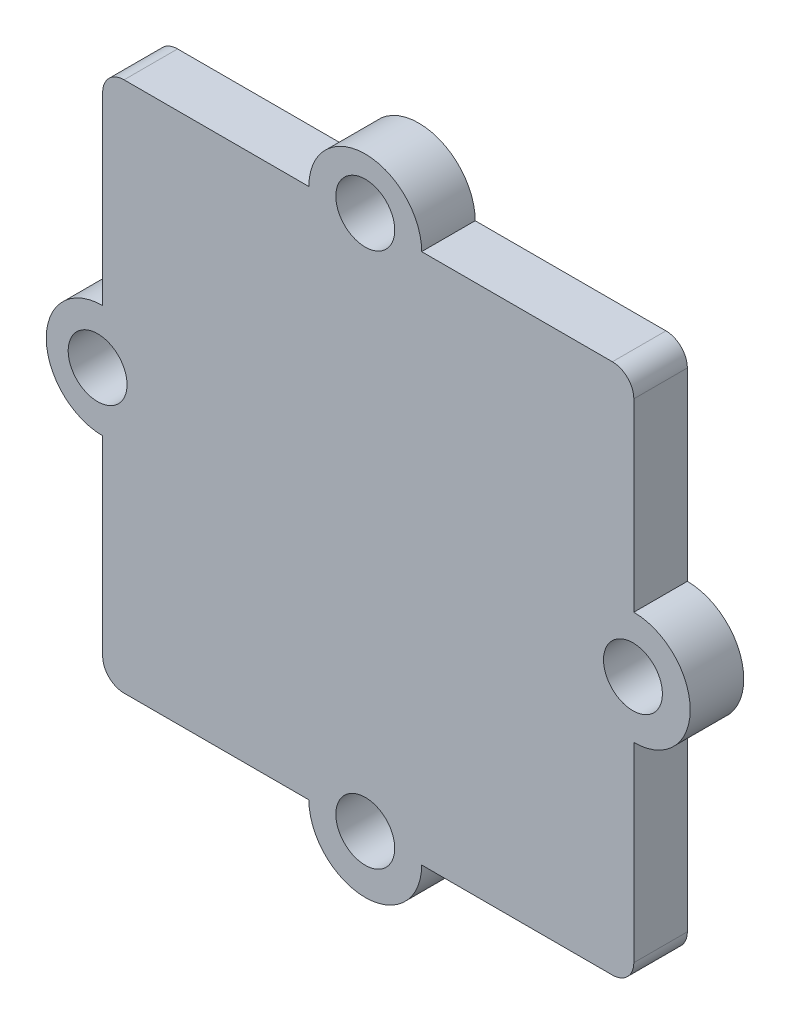
SolidWorks part; units mm, degrees
ref_plane "Front Plane" through (0, 0, 0) normal (0, 0, 1) x (1, 0, 0)
ref_plane "Top Plane" through (0, 0, 0) normal (0, 1, 0) x (1, 0, 0)
ref_plane "Right Plane" through (0, 0, 0) normal (1, 0, 0) x (0, 0, -1)
ref_plane "Plane1" through (0, 0, -2) normal (0, 0, -1) x (-1, 0, 0)
sketch "Sketch1" plane through (0, 0, -2) normal (0, 0, -1) x (-1, 0, 0)
  line L0 (-1.9169, 8.9003) -> (-9.843, 8.9003)
  line L1 (-9.843, 8.9003) -> (-9.843, 1.1965)
  line L2 (-9.843, -3.0174) -> (-9.843, -10.9434)
  line L3 (-9.843, -10.9434) -> (-1.9169, -10.9434)
  line L4 (2.2969, -10.9434) -> (10.0007, -10.9434)
  line L5 (10.0007, -10.9434) -> (10.0007, -3.0174)
  line L6 (10.0007, 1.1965) -> (10.0007, 8.9003)
  line L7 (10.0007, 8.9003) -> (2.2969, 8.9003)
  arc A0 (2.2969, 8.9003) -> (-1.9169, 8.9003) centre (0.19, 8.9003) ccw
  arc A1 (-9.843, 1.1965) -> (-9.843, -3.0174) centre (-9.843, -0.9104) ccw
  arc A2 (-1.9169, -10.9434) -> (2.2969, -10.9434) centre (0.19, -10.9434) ccw
  arc A3 (10.0007, -3.0174) -> (10.0007, 1.1965) centre (10.0007, -0.9104) ccw
  dimension "D1" = 19.8438
  dimension "D2" = 19.8438
extrude "Boss-Extrude1" add sketch "Sketch1" against normal blind 2
sketch "Sketch2" plane through (0, 0, 0) normal (0, 0, 1) x (1, 0, 0)
  line L0 (-2.6705, -4.0209) -> (-2.6705, -6.1294)
  line L1 (-2.6705, -6.1294) -> (-8.4533, -6.1294)
  line L2 (-8.4533, -6.1294) -> (-8.4533, 4.6027)
  line L3 (-8.4533, 4.6027) -> (-2.6705, 4.6027)
  line L4 (-2.6705, 4.6027) -> (-2.6705, 2.4942)
  line L5 (-2.6705, 2.4942) -> (-3.6705, 2.4942)
  line L6 (-3.6705, 2.4942) -> (-3.6705, 3.6027)
  line L7 (-3.6705, 3.6027) -> (-7.4533, 3.6027)
  line L8 (-7.4533, 3.6027) -> (-7.4533, -5.1294)
  line L9 (-7.4533, -5.1294) -> (-3.6705, -5.1294)
  line L10 (-3.6705, -5.1294) -> (-3.6705, -4.0209)
  line L11 (-3.6705, -4.0209) -> (-2.6705, -4.0209)
extrude "Boss-Extrude2" [suppressed] add sketch "Sketch2" along normal blind 8
sketch "Sketch3" plane through (0, 0, 0) normal (0, 0, 1) x (1, 0, 0)
  line L0 (-4.6569, -2.1142) -> (-5.7565, -2.1142)
  line L1 (-5.7565, -2.1142) -> (-5.7565, -1.3058)
  line L2 (-5.7565, -1.3058) -> (-4.6569, -1.3058)
  line L3 (-4.6569, -1.3058) -> (-4.6569, -2.1142)
extrude "Boss-Extrude3" [suppressed] add sketch "Sketch3" along normal blind 6
sketch "Sketch4" plane through (0, 0, 0) normal (0, 0, 1) x (1, 0, 0)
  line L0 (-4.6569, 1.8858) -> (-5.7565, 1.8858)
  line L1 (-5.7565, 1.8858) -> (-5.7565, 2.6942)
  line L2 (-5.7565, 2.6942) -> (-4.6569, 2.6942)
  line L3 (-4.6569, 2.6942) -> (-4.6569, 1.8858)
extrude "Boss-Extrude4" [suppressed] add sketch "Sketch4" along normal blind 6
sketch "Sketch5" plane through (0, 0, 0) normal (0, 0, 1) x (1, 0, 0)
  line L0 (-5.7565, -0.1142) -> (-5.7565, 0.6942)
  line L1 (-5.7565, 0.6942) -> (-4.6569, 0.6942)
  line L2 (-4.6569, 0.6942) -> (-4.6569, -0.1142)
  line L3 (-4.6569, -0.1142) -> (-5.7565, -0.1142)
extrude "Boss-Extrude5" [suppressed] add sketch "Sketch5" along normal blind 6
sketch "Sketch6" plane through (0, 0, 0) normal (0, 0, 1) x (1, 0, 0)
  line L0 (-4.6569, -3.3058) -> (-4.6569, -4.1142)
  line L1 (-4.6569, -4.1142) -> (-5.7565, -4.1142)
  line L2 (-5.7565, -4.1142) -> (-5.7565, -3.3058)
  line L3 (-5.7565, -3.3058) -> (-4.6569, -3.3058)
extrude "Boss-Extrude6" [suppressed] add sketch "Sketch6" along normal blind 6
hole_wizard "#1 Clearance Hole1" positions "Sketch11" profile "Sketch10" hole size "#1" standard "ANSI Inch" end condition through all
sketch "Sketch11" plane through (0, 0, -2) normal (0, 0, -1) x (-1, 0, 0)
  point P0 (0.1894, -10.9074)
  point P1 (0.1894, 9.0926)
  point P2 (10.1894, -0.9074)
  point P3 (-9.8106, -0.9074)
sketch "Sketch10" plane through (-0.1894, -10.9074, -2) normal (1, 0, 0) x (0, 1, 0)
  line L0 (0, 0) -> (0, 2)
  line L1 (0, 2) -> (1.1, 2)
  line L2 (1.1, 2) -> (1.1, 0)
  line L5 (1.1, 0) -> (0, 0)
  line L11 (0, -6.35) -> (0, 107.95) construction
  dimension "Thru Hole Dia." = 2.2
  dimension "Thru Hole Depth" = 2
chamfer "Chamfer1" [suppressed] distance 0.2 angle 45
fillet "Fillet1" radius 0.8 4 edges at (-10.0007, -10.9434, -1) (-10.0007, 8.9003, -1) (9.843, -10.9434, -1) (9.843, 8.9003, -1)
sketch "Sketch12" plane through (0, 0, 0) normal (0, 0, 1) x (1, 0, 0)
  line L0 (-0.1894, 9.0926) -> (-0.1894, -10.9074) construction
  circle A3 centre (-0.1894, 9.0926) radius 1.1 construction
  circle A4 centre (-0.1894, 9.0926) radius 1.1 construction
  dimension "D2" = 2.2
  dimension "D1" = 20
equation "\"groveHoleDiam\"= \"D2@Sketch12\""
equation "\"groveHoleBetween\"=0.78125"
equation "\"D1@Sketch1\"=\"groveHoleBetween\""
equation "\"D2@Sketch1\"=\"groveHoleBetween\""
